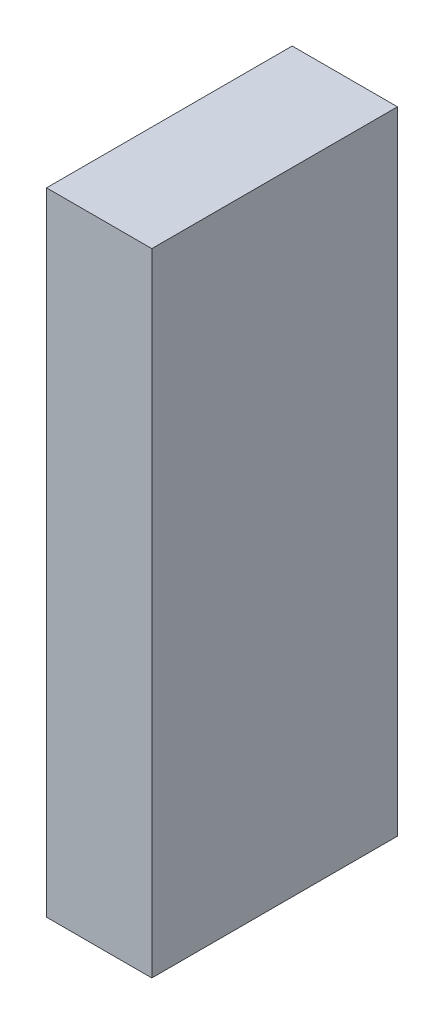
SolidWorks part; units mm, degrees
material "Pine"
ref_plane "Front Plane" through (0, 0, 0) normal (0, 0, 1) x (1, 0, 0)
ref_plane "Top Plane" through (0, 0, 0) normal (0, 1, 0) x (1, 0, 0)
ref_plane "Right Plane" through (0, 0, 0) normal (1, 0, 0) x (0, 0, -1)
sketch "Sketch1" plane through (0, 0, 0) normal (0, 1, 0) x (1, 0, 0)
  line L1 (0, 0) -> (38.1, 0)
  line L2 (0, 0) -> (0, 88.9)
  line L3 (0, 88.9) -> (38.1, 88.9)
  line L4 (38.1, 0) -> (38.1, 88.9)
  dimension "D1" = 38.1
  dimension "D2" = 88.9
extrude "Boss-Extrude1" add sketch "Sketch1" along normal blind 228.6
